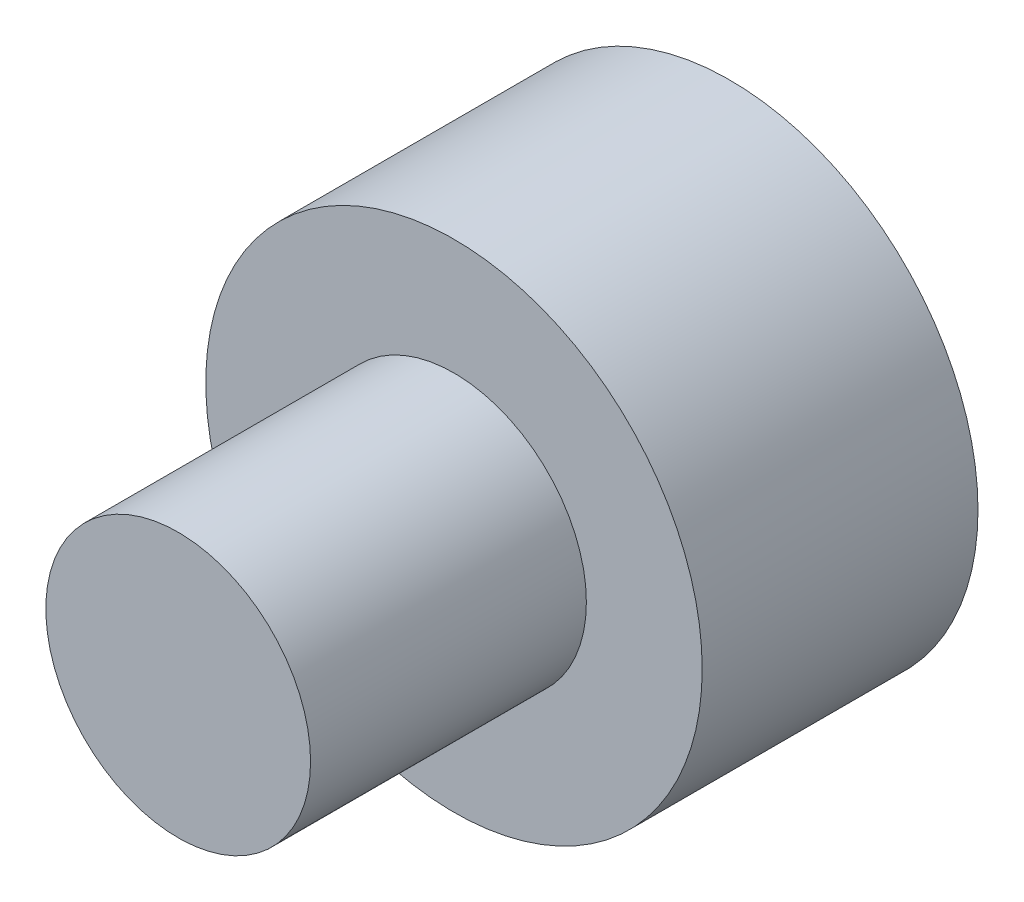
SolidWorks part; units mm, degrees
ref_plane "Спереди" through (0, 0, 0) normal (0, 0, 1) x (1, 0, 0)
ref_plane "Сверху" through (0, 0, 0) normal (0, 1, 0) x (1, 0, 0)
ref_plane "Справа" through (0, 0, 0) normal (1, 0, 0) x (0, 0, -1)
sketch "Эскиз1" plane through (0, 0, 0) normal (0, 0, 1) x (1, 0, 0)
  circle A0 centre (0, 0) radius 2.25
  dimension "D1" = 4.5
extrude "Бобышка-Вытянуть1" add sketch "Эскиз1" along normal blind 2.5
sketch "Эскиз2" plane through (0, 0, 2.5) normal (0, 0, 1) x (1, 0, 0)
  circle A0 centre (0, 0) radius 1.2
  dimension "D1" = 2.4
extrude "Бобышка-Вытянуть2" add sketch "Эскиз2" along normal blind 2.5
